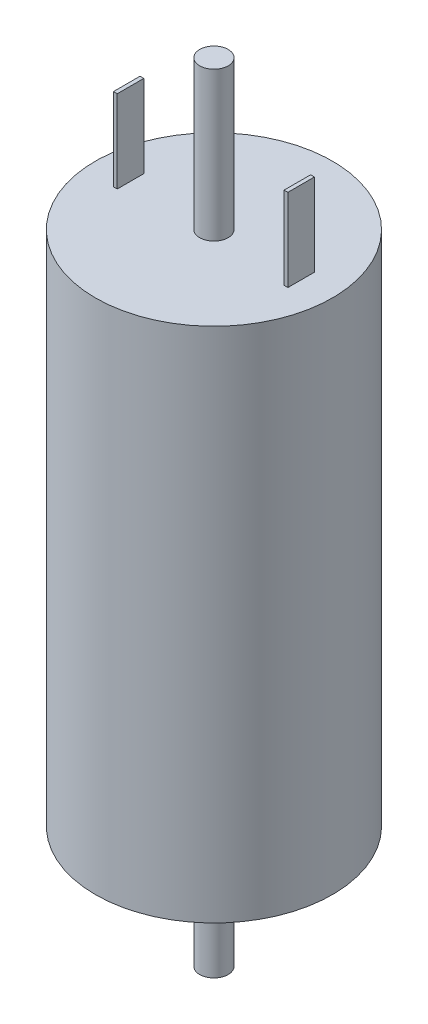
SolidWorks part; units mm, degrees
ref_plane "Front Plane" through (0, 0, 0) normal (0, 0, 1) x (1, 0, 0)
ref_plane "Top Plane" through (0, 0, 0) normal (0, 1, 0) x (1, 0, 0)
ref_plane "Right Plane" through (0, 0, 0) normal (1, 0, 0) x (0, 0, -1)
sketch "Sketch1" plane through (0, 0, 0) normal (0, 1, 0) x (1, 0, 0)
  circle A0 centre (0, 0) radius 12.5
  dimension "D1" = 25
extrude "Boss-Extrude1" add sketch "Sketch1" against normal blind 54.5
sketch "Sketch2" plane through (0, -54.5, 0) normal (0, -1, 0) x (1, 0, 0)
  circle A0 centre (0, 0) radius 1.5
  dimension "D1" = 3
extrude "Boss-Extrude2" add sketch "Sketch2" along normal blind 12.8
sketch "Sketch3" plane through (0, 0, 0) normal (0, 1, 0) x (1, 0, 0)
  circle A0 centre (0, 0) radius 1.5
  circle A1 centre (0, 0) radius 1.5 construction
extrude "Boss-Extrude3" add sketch "Sketch3" along normal blind 15.7
sketch "Sketch4" plane through (0, 0, 0) normal (0, 1, 0) x (1, 0, 0)
  line L0 (0, 0) -> (9, 0) construction
  line L1 (0, 0) -> (0, 12.5) construction
  line L2 (8.8, -1.4) -> (9.2, -1.4)
  line L3 (8.8, -1.4) -> (8.8, 1.4)
  line L4 (8.8, 1.4) -> (9.2, 1.4)
  line L5 (9.2, -1.4) -> (9.2, 1.4)
  line L6 (8.8, -1.4) -> (9.2, 1.4) construction
  line L7 (8.8, 1.4) -> (9.2, -1.4) construction
  line L8 (-8.8, -1.4) -> (-8.8, 1.4)
  line L9 (-8.8, -1.4) -> (-9.2, -1.4)
  line L10 (-9.2, -1.4) -> (-9.2, 1.4)
  line L11 (-8.8, 1.4) -> (-9.2, 1.4)
  circle A0 centre (0, 0) radius 12.5 construction
  dimension "D1" = 9
  dimension "D2" = 2.8
  dimension "D3" = 0.4
extrude "Boss-Extrude4" add sketch "Sketch4" along normal blind 8.7
sketch "Sketch5" plane through (0, -54.5, 0) normal (0, -1, 0) x (1, 0, 0)
  line L0 (0, 12.5) -> (0, -12.5) construction
  line L1 (-12.5, 0) -> (12.5, 0) construction
  line L2 (0, 0) -> (-7.3612, -4.25) construction
  circle A0 centre (0, 0) radius 12.5 construction
  circle A1 centre (0, 8.5) radius 1
  circle A2 centre (0, -8.5) radius 1
  circle A3 centre (0, 0) radius 8.5 construction
  circle A4 centre (-7.3612, -4.25) radius 1
  circle A5 centre (7.3612, -4.25) radius 1
  dimension "D1" = 2
  dimension "D2" = 60
extrude "Cut-Extrude1" cut sketch "Sketch5" against normal blind 2.9
sketch "Sketch6" plane through (0, -54.5, 0) normal (0, -1, 0) x (1, 0, 0)
  circle A0 centre (0, 0) radius 5
  dimension "D1" = 10
extrude "Boss-Extrude5" add sketch "Sketch6" along normal blind 2.9
